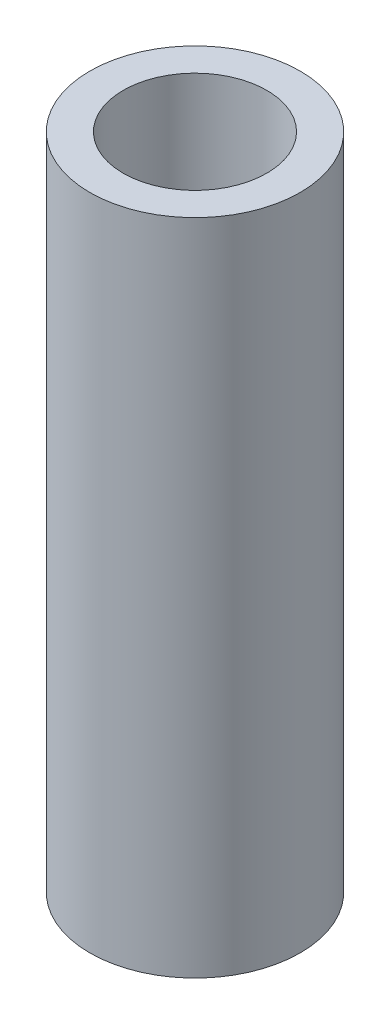
SolidWorks part; units mm, degrees
material "ABS"
ref_plane "Front Plane" through (0, 0, 0) normal (0, 0, 1) x (1, 0, 0)
ref_plane "Top Plane" through (0, 0, 0) normal (0, 1, 0) x (1, 0, 0)
ref_plane "Right Plane" through (0, 0, 0) normal (1, 0, 0) x (0, 0, -1)
sketch "Sketch1" plane through (0, 0, 0) normal (0, 1, 0) x (1, 0, 0)
  circle A0 centre (0, 0) radius 21.53
  circle A1 centre (0, 0) radius 31.53
  dimension "D1" = 43.06
  dimension "D2" = 63.06
extrude "Boss-Extrude1" add sketch "Sketch1" along normal blind 197.41
sketch "Sketch2" plane through (0, 0, 0) normal (1, 0, 0) x (0, 0, -1)
  line L0 (21.53, 197.41) -> (-21.53, 197.41) construction
  circle A0 centre (0, 132.71) radius 11.53
  circle A1 centre (0, 81.41) radius 11.53
  circle A2 centre (0, 30.11) radius 11.53
  dimension "D1" = 23.06
  dimension "D2" = 23.06
  dimension "D3" = 23.06
  dimension "D4" = 64.7
  dimension "D5" = 51.3
  dimension "D6" = 51.3
extrude "Cut-Extrude1" cut sketch "Sketch2" against normal through all
